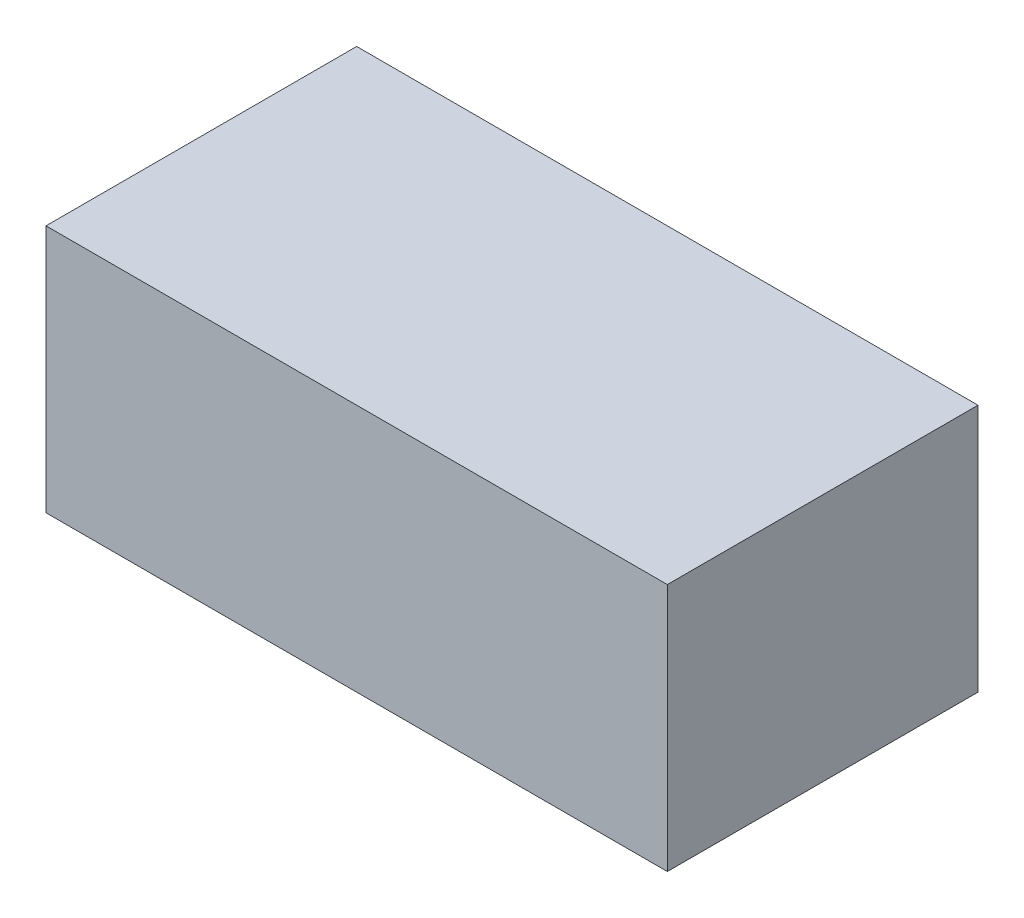
SolidWorks part; units mm, degrees
ref_plane "Front Plane" through (0, 0, 0) normal (0, 0, 1) x (1, 0, 0)
ref_plane "Top Plane" through (0, 0, 0) normal (0, 1, 0) x (1, 0, 0)
ref_plane "Right Plane" through (0, 0, 0) normal (1, 0, 0) x (0, 0, -1)
sketch "Sketch1" plane through (0, 0, 0) normal (0, 1, 0) x (1, 0, 0)
  line L1 (-50, 25) -> (50, 25)
  line L2 (-50, 25) -> (-50, -25)
  line L3 (-50, -25) -> (50, -25)
  line L4 (50, 25) -> (50, -25)
  line L5 (-50, 25) -> (50, -25) construction
  line L6 (-50, -25) -> (50, 25) construction
  point P0 (0, 0)
extrude "Boss-Extrude1" add sketch "Sketch1" along normal blind 40
